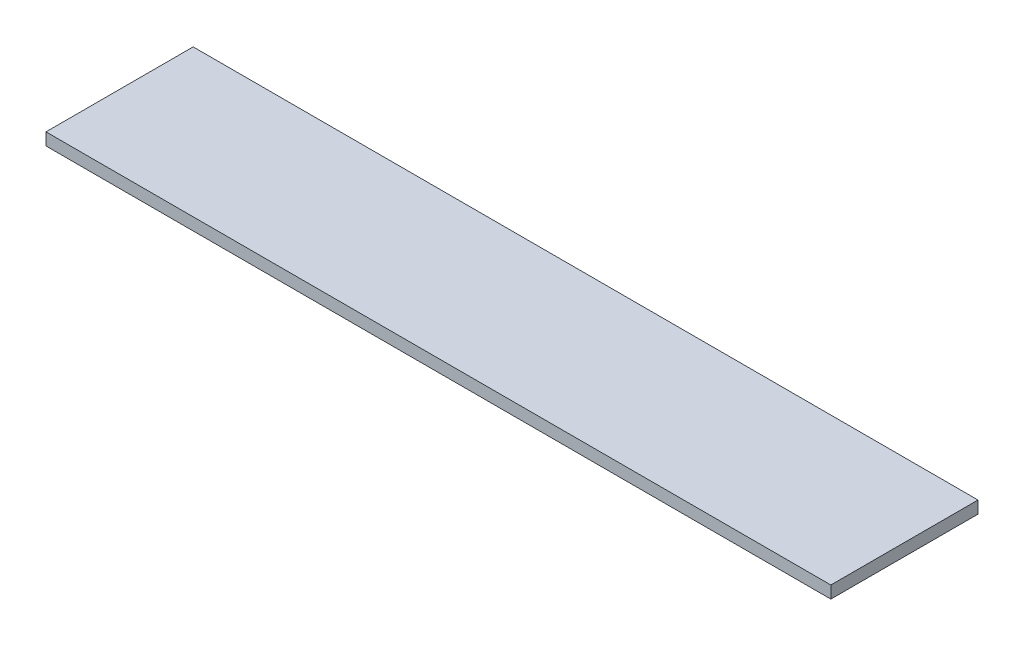
SolidWorks part; units mm, degrees
ref_plane "前视基准面" through (0, 0, 0) normal (0, 0, 1) x (1, 0, 0)
ref_plane "上视基准面" through (0, 0, 0) normal (0, 1, 0) x (1, 0, 0)
ref_plane "右视基准面" through (0, 0, 0) normal (1, 0, 0) x (0, 0, -1)
other "Configuration Table"
sketch "草图1" plane through (0, 0, 0) normal (0, 1, 0) x (1, 0, 0)
  line L1 (0, 0) -> (320, 0)
  line L2 (0, 0) -> (0, -60)
  line L3 (0, -60) -> (320, -60)
  line L4 (320, 0) -> (320, -60)
  dimension "D1" = 320
  dimension "D2" = 60
extrude "凸台-拉伸1" add sketch "草图1" along normal blind 5
